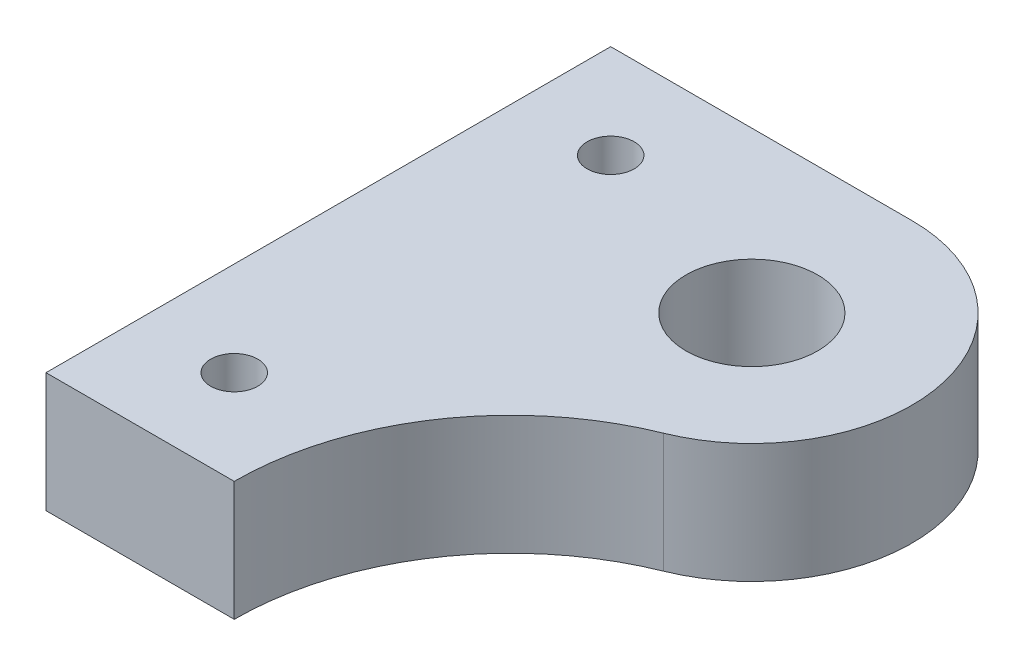
SolidWorks part; units mm, degrees
ref_plane "Front Plane" through (0, 0, 0) normal (0, 0, 1) x (1, 0, 0)
ref_plane "Top Plane" through (0, 0, 0) normal (0, 1, 0) x (1, 0, 0)
ref_plane "Right Plane" through (0, 0, 0) normal (1, 0, 0) x (0, 0, -1)
sketch "Sketch1" plane through (0, 0, 0) normal (0, 1, 0) x (1, 0, 0)
  line L1 (20, 0) -> (0, 0)
  line L2 (0, 0) -> (0, 60)
  line L3 (32, 60) -> (0, 60)
  line L4 (20, -25.9546) -> (20, 30.2072) construction
  line L5 (10, 0) -> (10, 10) construction
  line L6 (10, 60) -> (10, 50) construction
  line L7 (10, 10) -> (0, 10) construction
  arc A0 (20, 0) -> (38.3703, 27.2387) centre (49.3793, 0) cw
  arc A1 (38.3703, 27.2387) -> (32, 60) centre (32, 43) ccw
  circle A2 centre (32, 43) radius 7
  circle A3 centre (10, 10) radius 2.5
  circle A4 centre (10, 50) radius 2.5
  point P11 (25, 43)
  dimension "D3" = 14
  dimension "D5" = 10
  dimension "D6" = 5
  dimension "D1" = 20
  dimension "D2" = 60
  dimension "D4" = 5
extrude "Boss-Extrude1" add sketch "Sketch1" along normal mid plane 12.7
